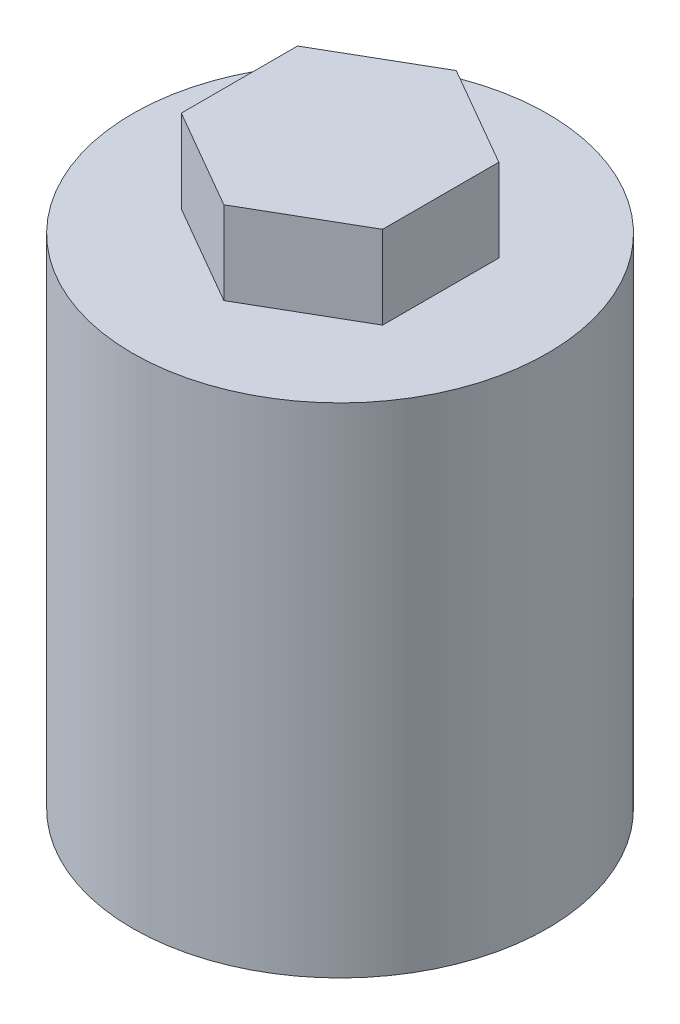
SolidWorks part; units mm, degrees
ref_plane "前视基准面" through (0, 0, 0) normal (0, 0, 1) x (1, 0, 0)
ref_plane "上视基准面" through (0, 0, 0) normal (0, 1, 0) x (1, 0, 0)
ref_plane "右视基准面" through (0, 0, 0) normal (1, 0, 0) x (0, 0, -1)
sketch "草图1" plane through (0, 0, 0) normal (0, 1, 0) x (1, 0, 0)
  circle A0 centre (0, 0) radius 25
  dimension "D1" = 50
extrude "凸台-拉伸1" add sketch "草图1" along normal blind 60
sketch "草图2" plane through (0, 60, 0) normal (0, 1, 0) x (1, 0, 0)
  line L1 (0, 14) -> (-12.1244, 7)
  line L2 (-12.1244, 7) -> (-12.1244, -7)
  line L3 (-12.1244, -7) -> (0, -14)
  line L4 (0, -14) -> (12.1244, -7)
  line L5 (12.1244, -7) -> (12.1244, 7)
  line L6 (12.1244, 7) -> (0, 14)
  circle A0 centre (0, 0) radius 12.1244 construction
  dimension "D1" = 28
extrude "凸台-拉伸2" add sketch "草图2" along normal blind 10
